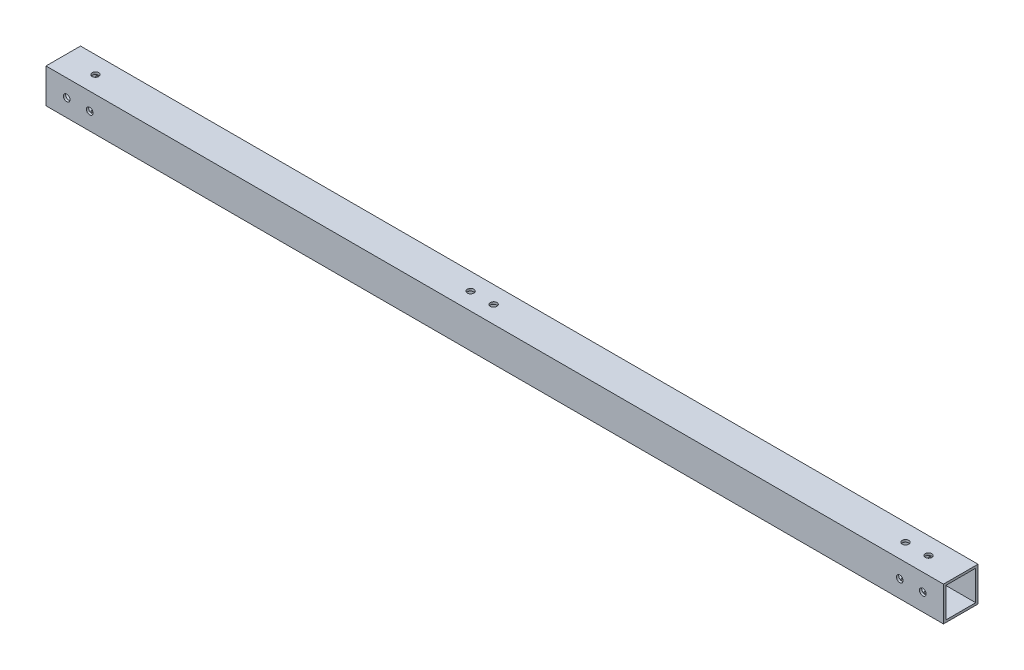
SolidWorks part; units mm, degrees
material "Thornel Mat VMA"
ref_plane "前视基准面" through (0, 0, 0) normal (0, 0, 1) x (1, 0, 0)
ref_plane "上视基准面" through (0, 0, 0) normal (0, 1, 0) x (1, 0, 0)
ref_plane "右视基准面" through (0, 0, 0) normal (1, 0, 0) x (0, 0, -1)
other "Configuration Table"
sketch "草图1" plane through (0, 0, 0) normal (1, 0, 0) x (0, 0, -1)
  line L0 (-6.5, -6.5) -> (-6.5, 6.5)
  line L1 (-7.5, -7.5) -> (7.5, -7.5)
  line L2 (-7.5, -7.5) -> (-7.5, 7.5)
  line L3 (-7.5, 7.5) -> (7.5, 7.5)
  line L4 (7.5, -7.5) -> (7.5, 7.5)
  line L5 (-7.5, -7.5) -> (7.5, 7.5) construction
  line L6 (-7.5, 7.5) -> (7.5, -7.5) construction
  line L7 (-6.5, 6.5) -> (6.5, 6.5)
  line L8 (6.5, -6.5) -> (6.5, 6.5)
  line L9 (-6.5, -6.5) -> (6.5, -6.5)
  point P0 (0, 0)
  dimension "D1" = 15
  dimension "D2" = 15
  dimension "D3" = 1
extrude "凸台-拉伸1" add sketch "草图1" along normal blind 390
sketch "草图2" plane through (0, 7.5, 0) normal (0, 1, 0) x (1, 0, 0)
  line L0 (-12.7348, 0) -> (402.9498, 0) construction
  line L1 (0, 7.5) -> (0, -7.5) construction
  circle A0 centre (14, 0) radius 1.45 construction
  circle A1 centre (14, 0) radius 1.45
  circle A2 centre (366, 0) radius 1.45 construction
  circle A3 centre (376, 0) radius 1.45 construction
  circle A4 centre (366, 0) radius 1.45
  circle A5 centre (376, 0) radius 1.45
  circle A6 centre (177, 0) radius 1.45
  circle A7 centre (187, 0) radius 1.45
  dimension "D2" = 187
  dimension "D3" = 2.9
  dimension "D4" = 2.9
  dimension "D1" = 177
extrude "切除-拉伸1" cut sketch "草图2" against normal through all
sketch "草图3" plane through (0, 0, -7.5) normal (0, 0, -1) x (-1, 0, 0)
  circle A0 centre (-381, 0) radius 1.45 construction
  circle A1 centre (-371, 0) radius 1.45 construction
  circle A2 centre (-9, 0) radius 1.45 construction
  circle A3 centre (-19, 0) radius 1.45 construction
  circle A4 centre (-381, 0) radius 1.45
  circle A5 centre (-371, 0) radius 1.45
  circle A6 centre (-9, 0) radius 1.45
  circle A7 centre (-19, 0) radius 1.45
extrude "切除-拉伸2" cut sketch "草图3" against normal through all
